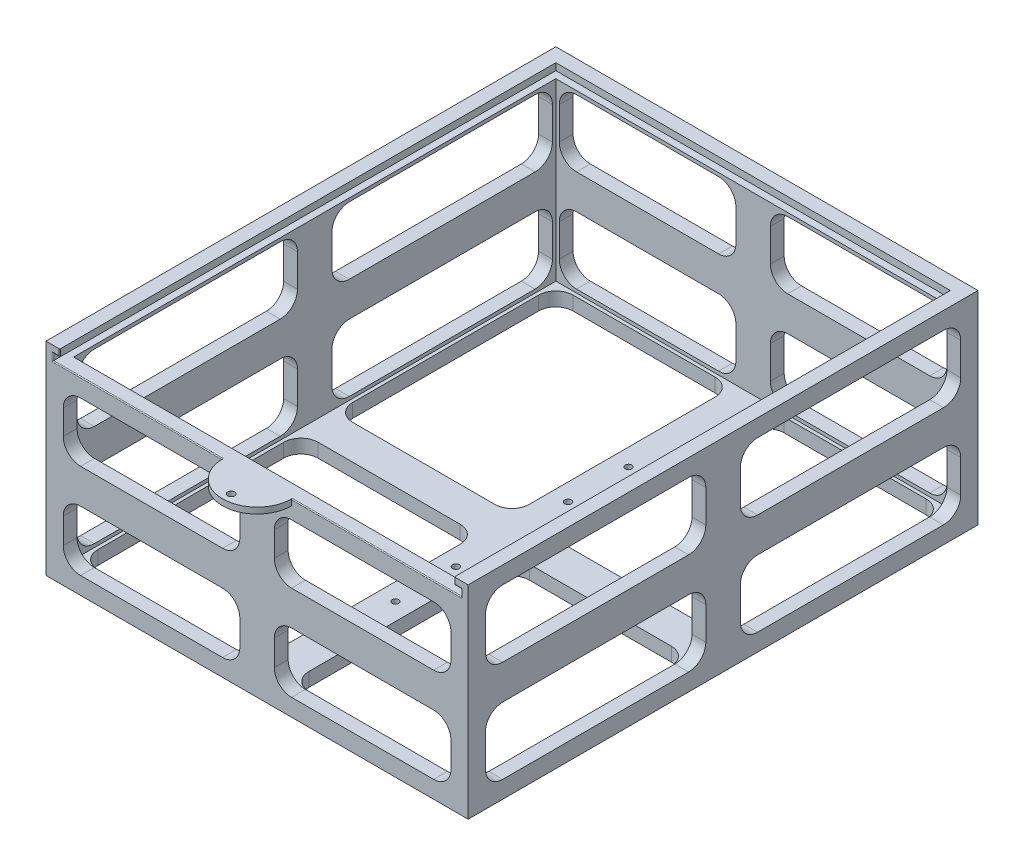
SolidWorks part; units mm, degrees
ref_plane "Front Plane" through (0, 0, 0) normal (0, 0, 1) x (1, 0, 0)
ref_plane "Top Plane" through (0, 0, 0) normal (0, 1, 0) x (1, 0, 0)
ref_plane "Right Plane" through (0, 0, 0) normal (1, 0, 0) x (0, 0, -1)
sketch "Sketch1" plane through (0, 0, 0) normal (0, 1, 0) x (1, 0, 0)
  line L1 (-122.3, -147.7) -> (122.3, -147.7)
  line L2 (-122.3, -147.7) -> (-122.3, 147.7)
  line L3 (-122.3, 147.7) -> (122.3, 147.7)
  line L4 (122.3, -147.7) -> (122.3, 147.7)
  line L5 (-122.3, -147.7) -> (122.3, 147.7) construction
  line L6 (-122.3, 147.7) -> (122.3, -147.7) construction
  point P0 (0, 0)
  dimension "D1" = 244.6
  dimension "D2" = 295.4
extrude "Boss-Extrude1" add sketch "Sketch1" along normal blind 117.6
shell "Shell1" thickness 8
sketch "Sketch5" plane through (122.3, 0, 0) normal (1, 0, 0) x (0, 0, -1)
  line L0 (-147.7, 117.6) -> (147.7, 0) construction
  line L1 (147.7, 117.6) -> (-147.7, 0) construction
  line L2 (-147.7, 117.6) -> (147.7, 117.6) construction
  line L3 (-137.7, 10) -> (137.7, 10)
  line L4 (-137.7, 10) -> (-137.7, 107.6)
  line L5 (-137.7, 107.6) -> (137.7, 107.6)
  line L6 (137.7, 10) -> (137.7, 107.6)
  line L7 (-137.7, 10) -> (137.7, 107.6) construction
  line L8 (-137.7, 107.6) -> (137.7, 10) construction
  line L9 (147.7, 117.6) -> (147.7, 0) construction
  point P8 (0, 58.8)
  dimension "D1" = 10
  dimension "D2" = 10
sketch "Sketch6" plane through (0, 0, 147.7) normal (0, 0, 1) x (1, 0, 0)
  line L0 (-122.3, 0) -> (122.3, 0) construction
  line L1 (-122.3, 117.6) -> (-122.3, 0) construction
  line L2 (-122.3, 117.6) -> (122.3, 117.6) construction
  line L3 (-112.3, 10) -> (112.3, 10)
  line L4 (-112.3, 10) -> (-112.3, 107.6)
  line L5 (-112.3, 107.6) -> (112.3, 107.6)
  line L6 (112.3, 10) -> (112.3, 107.6)
  line L7 (-112.3, 10) -> (112.3, 107.6) construction
  line L8 (-112.3, 107.6) -> (112.3, 10) construction
  line L9 (122.3, 10) -> (122.3, 107.6) construction
  point P8 (0, 58.8)
  dimension "D1" = 10
  dimension "D2" = 10
  dimension "D3" = 10
  dimension "D4" = 10
sketch "Sketch8" plane through (0, 0, 147.7) normal (0, 0, 1) x (1, 0, 0)
  line L0 (122.3, 117.6) -> (122.3, 0) construction
  line L1 (-114.3, 109.6) -> (114.3, 109.6)
  line L2 (-114.3, 109.6) -> (-114.3, 117.6)
  line L3 (-114.3, 117.6) -> (114.3, 117.6)
  line L4 (114.3, 109.6) -> (114.3, 117.6)
  line L5 (-122.3, 117.6) -> (-122.3, 0) construction
  line L6 (-122.3, 117.6) -> (122.3, 117.6) construction
  dimension "D1" = 8
  dimension "D2" = 8
  dimension "D3" = 0
  dimension "D4" = 8
extrude "Cut-Extrude1" cut sketch "Sketch8" against normal blind 8
sketch "Sketch9" plane through (0, 0, 147.7) normal (0, 0, 1) x (1, 0, 0)
  line L0 (122.3, 117.6) -> (122.3, 0) construction
  line L1 (-118.3, 109.6) -> (118.3, 109.6)
  line L2 (-118.3, 109.6) -> (-118.3, 113.6)
  line L3 (-118.3, 113.6) -> (118.3, 113.6)
  line L4 (118.3, 109.6) -> (118.3, 113.6)
  line L6 (-122.3, 117.6) -> (-122.3, 0) construction
  line L7 (-122.3, 117.6) -> (-114.3, 117.6) construction
  dimension "D1" = 4
  dimension "D2" = 4
  dimension "D3" = 8
  dimension "D4" = 4
extrude "Cut-Extrude2" cut sketch "Sketch9" against normal blind 291.4
sketch "Sketch10" plane through (0, 109.6, 0) normal (0, 1, 0) x (1, 0, 0)
  line L0 (-114.3, -147.7) -> (114.3, -147.7) construction
  line L1 (-20, -147.7) -> (20, -147.7)
  line L2 (-122.3, 147.7) -> (-122.3, -147.7) construction
  line L3 (122.3, -147.7) -> (122.3, 147.7) construction
  arc A0 (-20, -147.7) -> (20, -147.7) centre (0, -147.7) ccw
  dimension "D1" = 20
  dimension "D2" = 122.3
  dimension "D3" = 122.3
extrude "Boss-Extrude2" add sketch "Sketch10" against normal blind 3.5
sketch "Sketch12" plane through (0, 109.6, 0) normal (0, 1, 0) x (1, 0, 0)
  circle A0 centre (0, -162.7) radius 2
  arc A1 (-20, -147.7) -> (20, -147.7) centre (0, -147.7) ccw construction
  dimension "D2" = 4
  dimension "D1" = 15
extrude "Cut-Extrude3" cut sketch "Sketch12" against normal blind 3.5
fillet "Fillet1" radius 0.5 8 edges at (-114.3, 115.6, 147.7) (114.3, 115.6, 147.7) (116.3, 113.6, 147.7) (118.3, 111.6, 147.7) (69.15, 109.6, 147.7) (-69.15, 109.6, 147.7) (-116.3, 113.6, 147.7) (-118.3, 111.6, 147.7)
sketch "Sketch13" plane through (0, 0, 0) normal (0, -1, 0) x (1, 0, 0)
  line L0 (0, 0) -> (0, -147.7) construction
  line L1 (-122.3, 147.7) -> (122.3, -147.7) construction
  line L2 (-122.3, -147.7) -> (122.3, -147.7) construction
  line L3 (0, 0) -> (0, 147.7) construction
  line L4 (-122.3, 147.7) -> (122.3, 147.7) construction
  line L6 (-7.25, -72.5) -> (7.25, -72.5)
  line L7 (-7.25, -72.5) -> (-7.25, -27.5)
  line L8 (-7.25, -27.5) -> (7.25, -27.5)
  line L9 (7.25, -72.5) -> (7.25, -27.5)
  line L10 (-7.25, -72.5) -> (7.25, -27.5) construction
  line L11 (-7.25, -27.5) -> (7.25, -72.5) construction
  line L12 (-7.25, 27.5) -> (7.25, 27.5)
  line L13 (-7.25, 27.5) -> (-7.25, 72.5)
  line L14 (-7.25, 72.5) -> (7.25, 72.5)
  line L15 (7.25, 27.5) -> (7.25, 72.5)
  line L16 (-7.25, 27.5) -> (7.25, 72.5) construction
  line L17 (-7.25, 72.5) -> (7.25, 27.5) construction
  point P6 (0, -50)
  point P14 (0, 50)
  dimension "D1" = 50
  dimension "D2" = 147.7
  dimension "D3" = 50
  dimension "D4" = 14.5
  dimension "D5" = 14.5
  dimension "D6" = 45
  dimension "D7" = 45
extrude "Boss-Extrude3" add sketch "Sketch13" against normal blind 8
sketch "Sketch14" plane through (0, 0, 0) normal (0, -1, 0) x (1, 0, 0)
  line L4 (20, 147.7) -> (-20, 147.7) construction
  line L5 (122.3, -147.7) -> (-122.3, -147.7) construction
  circle A0 centre (0, 67.5) radius 1.95
  circle A1 centre (0, 32.5) radius 1.95
  circle A2 centre (0, -32.5) radius 1.95
  circle A3 centre (0, -67.5) radius 1.95
  dimension "D1" = 3.9
  dimension "D2" = 3.9
  dimension "D3" = 3.9
  dimension "D4" = 3.9
  dimension "D9" = 80.2
  dimension "D10" = 35
  dimension "D11" = 65
  dimension "D12" = 35
  dimension "D13" = 80.2
extrude "Cut-Extrude4" cut sketch "Sketch14" against normal blind 8
sketch "Sketch16" plane through (-122.3, 0, 0) normal (-1, 0, 0) x (0, 0, 1)
  line L0 (0, 117.6) -> (0, 0) construction
  line L1 (-127.7, 107.6) -> (-20, 107.6)
  line L2 (-137.7, 97.6) -> (-137.7, 78.8)
  line L3 (-127.7, 68.8) -> (-20, 68.8)
  line L4 (-10, 97.6) -> (-10, 78.8)
  line L5 (-127.7, 48.8) -> (-20, 48.8)
  line L6 (-137.7, 38.8) -> (-137.7, 20)
  line L7 (-127.7, 10) -> (-20, 10)
  line L8 (-10, 38.8) -> (-10, 20)
  line L9 (20, 107.6) -> (127.7, 107.6)
  line L10 (10, 97.6) -> (10, 78.8)
  line L11 (20, 68.8) -> (127.7, 68.8)
  line L12 (137.7, 97.6) -> (137.7, 78.8)
  line L13 (20, 48.8) -> (127.7, 48.8)
  line L14 (10, 38.8) -> (10, 20)
  line L15 (20, 10) -> (127.7, 10)
  line L16 (137.7, 38.8) -> (137.7, 20)
  line L17 (-147.7, 117.6) -> (147.7, 117.6) construction
  line L18 (-147.7, 0) -> (147.7, 0) construction
  line L19 (-147.7, 58.8) -> (147.7, 58.8) construction
  line L20 (-147.7, 117.6) -> (-147.7, 0) construction
  line L21 (147.7, 117.6) -> (147.7, 0) construction
  arc A0 (10, 78.8) -> (20, 68.8) centre (20, 78.8) ccw
  arc A1 (20, 107.6) -> (10, 97.6) centre (20, 97.6) ccw
  arc A2 (127.7, 107.6) -> (137.7, 97.6) centre (127.7, 97.6) cw
  arc A3 (127.7, 68.8) -> (137.7, 78.8) centre (127.7, 78.8) ccw
  arc A4 (127.7, 10) -> (137.7, 20) centre (127.7, 20) ccw
  arc A5 (127.7, 48.8) -> (137.7, 38.8) centre (127.7, 38.8) cw
  arc A6 (20, 48.8) -> (10, 38.8) centre (20, 38.8) ccw
  arc A7 (10, 20) -> (20, 10) centre (20, 20) ccw
  arc A8 (-20, 10) -> (-10, 20) centre (-20, 20) ccw
  arc A9 (-137.7, 20) -> (-127.7, 10) centre (-127.7, 20) ccw
  arc A10 (-127.7, 48.8) -> (-137.7, 38.8) centre (-127.7, 38.8) ccw
  arc A11 (-20, 48.8) -> (-10, 38.8) centre (-20, 38.8) cw
  arc A12 (-20, 68.8) -> (-10, 78.8) centre (-20, 78.8) ccw
  arc A13 (-137.7, 78.8) -> (-127.7, 68.8) centre (-127.7, 78.8) ccw
  arc A14 (-20, 107.6) -> (-10, 97.6) centre (-20, 97.6) cw
  arc A15 (-127.7, 107.6) -> (-137.7, 97.6) centre (-127.7, 97.6) ccw
  dimension "D17" = 10
  dimension "D1" = 20
  dimension "D2" = 10
  dimension "D3" = 10
  dimension "D4" = 10
  dimension "D5" = 10
  dimension "D6" = 20
  dimension "D7" = 10
  dimension "D8" = 20
  dimension "D9" = 10
  dimension "D10" = 20
  dimension "D11" = 10
  dimension "D12" = 10
  dimension "D13" = 10
  dimension "D14" = 10
  dimension "D15" = 10
  dimension "D16" = 10
extrude "Cut-Extrude5" cut sketch "Sketch16" against normal blind 300
sketch "Sketch17" plane through (0, 0, -147.7) normal (0, 0, -1) x (-1, 0, 0)
  line L0 (0, 117.6) -> (0, 0) construction
  line L1 (-122.3, 117.6) -> (122.3, 117.6) construction
  line L2 (-122.3, 58.8) -> (122.3, 58.8) construction
  line L3 (-122.3, 117.6) -> (-122.3, 0) construction
  line L4 (122.3, 117.6) -> (122.3, 0) construction
  line L5 (-122.3, 0) -> (122.3, 0) construction
  line L6 (-102.3, 107.6) -> (-20, 107.6)
  line L7 (-112.3, 97.6) -> (-112.3, 78.8)
  line L8 (-102.3, 68.8) -> (-20, 68.8)
  line L9 (-10, 97.6) -> (-10, 78.8)
  line L10 (-102.3, 48.8) -> (-20, 48.8)
  line L11 (-112.3, 38.8) -> (-112.3, 20)
  line L12 (-102.3, 10) -> (-20, 10)
  line L13 (-10, 38.8) -> (-10, 20)
  line L14 (20, 107.6) -> (102.3, 107.6)
  line L15 (10, 97.6) -> (10, 78.8)
  line L16 (20, 68.8) -> (102.3, 68.8)
  line L17 (112.3, 97.6) -> (112.3, 78.8)
  line L18 (20, 48.8) -> (102.3, 48.8)
  line L19 (10, 38.8) -> (10, 20)
  line L20 (20, 10) -> (102.3, 10)
  line L21 (112.3, 38.8) -> (112.3, 20)
  arc A0 (102.3, 68.8) -> (112.3, 78.8) centre (102.3, 78.8) ccw
  arc A1 (102.3, 107.6) -> (112.3, 97.6) centre (102.3, 97.6) cw
  arc A2 (20, 107.6) -> (10, 97.6) centre (20, 97.6) ccw
  arc A3 (10, 78.8) -> (20, 68.8) centre (20, 78.8) ccw
  arc A4 (102.3, 10) -> (112.3, 20) centre (102.3, 20) ccw
  arc A5 (102.3, 48.8) -> (112.3, 38.8) centre (102.3, 38.8) cw
  arc A6 (20, 48.8) -> (10, 38.8) centre (20, 38.8) ccw
  arc A7 (10, 20) -> (20, 10) centre (20, 20) ccw
  arc A8 (-20, 10) -> (-10, 20) centre (-20, 20) ccw
  arc A9 (-20, 48.8) -> (-10, 38.8) centre (-20, 38.8) cw
  arc A10 (-112.3, 20) -> (-102.3, 10) centre (-102.3, 20) ccw
  arc A11 (-102.3, 48.8) -> (-112.3, 38.8) centre (-102.3, 38.8) ccw
  arc A12 (-20, 68.8) -> (-10, 78.8) centre (-20, 78.8) ccw
  arc A13 (-20, 107.6) -> (-10, 97.6) centre (-20, 97.6) cw
  arc A14 (-112.3, 78.8) -> (-102.3, 68.8) centre (-102.3, 78.8) ccw
  arc A15 (-102.3, 107.6) -> (-112.3, 97.6) centre (-102.3, 97.6) ccw
  dimension "D17" = 10
  dimension "D1" = 10
  dimension "D2" = 10
  dimension "D3" = 10
  dimension "D4" = 10
  dimension "D5" = 10
  dimension "D6" = 10
  dimension "D7" = 10
  dimension "D8" = 10
  dimension "D9" = 10
  dimension "D10" = 10
  dimension "D11" = 10
  dimension "D12" = 10
  dimension "D13" = 10
  dimension "D14" = 10
  dimension "D15" = 10
  dimension "D16" = 10
extrude "Cut-Extrude6" cut sketch "Sketch17" against normal blind 8
sketch "Sketch18" plane through (0, 0, 0) normal (0, -1, 0) x (1, 0, 0)
  line L0 (0, 147.7) -> (0, -147.7) construction
  line L1 (20, 147.7) -> (-20, 147.7) construction
  line L2 (122.3, -147.7) -> (-122.3, -147.7) construction
  line L3 (-122.3, 0) -> (122.3, 0) construction
  line L4 (-122.3, -147.7) -> (-122.3, 147.7) construction
  line L5 (122.3, 147.7) -> (122.3, -147.7) construction
  line L6 (-122.3, 147.7) -> (122.3, 147.7) construction
  line L7 (-102.3, 137.7) -> (-20, 137.7)
  line L8 (-112.3, 127.7) -> (-112.3, 20)
  line L9 (-102.3, 10) -> (-20, 10)
  line L10 (-10, 127.7) -> (-10, 20)
  line L11 (-102.3, -10) -> (-20, -10)
  line L12 (-112.3, -20) -> (-112.3, -127.7)
  line L13 (-102.3, -137.7) -> (-20, -137.7)
  line L14 (-10, -20) -> (-10, -127.7)
  line L15 (20, 137.7) -> (102.3, 137.7)
  line L16 (10, 127.7) -> (10, 20)
  line L17 (20, 10) -> (102.3, 10)
  line L18 (112.3, 127.7) -> (112.3, 20)
  line L19 (20, -10) -> (102.3, -10)
  line L20 (10, -20) -> (10, -127.7)
  line L21 (20, -137.7) -> (102.3, -137.7)
  line L22 (112.3, -20) -> (112.3, -127.7)
  arc A0 (10, -127.7) -> (20, -137.7) centre (20, -127.7) ccw
  arc A1 (102.3, -137.7) -> (112.3, -127.7) centre (102.3, -127.7) ccw
  arc A2 (102.3, -10) -> (112.3, -20) centre (102.3, -20) cw
  arc A3 (20, -10) -> (10, -20) centre (20, -20) ccw
  arc A4 (-20, -137.7) -> (-10, -127.7) centre (-20, -127.7) ccw
  arc A5 (-112.3, -127.7) -> (-102.3, -137.7) centre (-102.3, -127.7) ccw
  arc A6 (-20, -10) -> (-10, -20) centre (-20, -20) cw
  arc A7 (-102.3, -10) -> (-112.3, -20) centre (-102.3, -20) ccw
  arc A8 (102.3, 137.7) -> (112.3, 127.7) centre (102.3, 127.7) cw
  arc A9 (102.3, 10) -> (112.3, 20) centre (102.3, 20) ccw
  arc A10 (10, 20) -> (20, 10) centre (20, 20) ccw
  arc A11 (20, 137.7) -> (10, 127.7) centre (20, 127.7) ccw
  arc A12 (-20, 137.7) -> (-10, 127.7) centre (-20, 127.7) cw
  arc A13 (-20, 10) -> (-10, 20) centre (-20, 20) ccw
  arc A14 (-112.3, 20) -> (-102.3, 10) centre (-102.3, 20) ccw
  arc A15 (-102.3, 137.7) -> (-112.3, 127.7) centre (-102.3, 127.7) ccw
  dimension "D17" = 10
  dimension "D1" = 10
  dimension "D2" = 10
  dimension "D3" = 10
  dimension "D4" = 10
  dimension "D5" = 10
  dimension "D6" = 10
  dimension "D7" = 10
  dimension "D8" = 10
  dimension "D9" = 10
  dimension "D10" = 10
  dimension "D11" = 10
  dimension "D12" = 10
  dimension "D13" = 10
  dimension "D14" = 10
  dimension "D15" = 10
  dimension "D16" = 10
extrude "Cut-Extrude7" cut sketch "Sketch18" against normal blind 8
sketch "Sketch19" plane through (0, 0, 147.7) normal (0, 0, 1) x (1, 0, 0)
  line L0 (0, 109.6) -> (0, 0) construction
  line L1 (-118.3, 109.6) -> (118.3, 109.6) construction
  line L2 (0, 54.8) -> (-122.3, 54.8) construction
  line L3 (-122.3, 117.6) -> (-122.3, 0) construction
  line L4 (0, 54.8) -> (122.3, 54.8) construction
  line L5 (122.3, 117.6) -> (122.3, 0) construction
  line L6 (-20, 109.1) -> (-118.8, 109.1) construction
  line L7 (-102.3, 99.1) -> (-20, 99.1)
  line L8 (-112.3, 89.1) -> (-112.3, 74.8)
  line L9 (-102.3, 64.8) -> (-20, 64.8)
  line L10 (-10, 89.1) -> (-10, 74.8)
  line L11 (20, 99.1) -> (102.3, 99.1)
  line L12 (10, 89.1) -> (10, 74.8)
  line L13 (20, 64.8) -> (102.3, 64.8)
  line L14 (112.3, 89.1) -> (112.3, 74.8)
  line L15 (-102.3, 44.8) -> (-20, 44.8)
  line L16 (-112.3, 34.8) -> (-112.3, 20)
  line L17 (-102.3, 10) -> (-20, 10)
  line L18 (-10, 34.8) -> (-10, 20)
  line L19 (20, 44.8) -> (102.3, 44.8)
  line L20 (10, 34.8) -> (10, 20)
  line L21 (20, 10) -> (102.3, 10)
  line L22 (112.3, 34.8) -> (112.3, 20)
  line L23 (118.8, 109.1) -> (20, 109.1) construction
  line L24 (-122.3, 0) -> (122.3, 0) construction
  arc A0 (102.3, 99.1) -> (112.3, 89.1) centre (102.3, 89.1) cw
  arc A1 (102.3, 64.8) -> (112.3, 74.8) centre (102.3, 74.8) ccw
  arc A2 (102.3, 10) -> (112.3, 20) centre (102.3, 20) ccw
  arc A3 (102.3, 44.8) -> (112.3, 34.8) centre (102.3, 34.8) cw
  arc A4 (10, 20) -> (20, 10) centre (20, 20) ccw
  arc A5 (20, 44.8) -> (10, 34.8) centre (20, 34.8) ccw
  arc A6 (-20, 44.8) -> (-10, 34.8) centre (-20, 34.8) cw
  arc A7 (-20, 10) -> (-10, 20) centre (-20, 20) ccw
  arc A8 (-112.3, 20) -> (-102.3, 10) centre (-102.3, 20) ccw
  arc A9 (-102.3, 44.8) -> (-112.3, 34.8) centre (-102.3, 34.8) ccw
  arc A10 (10, 74.8) -> (20, 64.8) centre (20, 74.8) ccw
  arc A11 (20, 99.1) -> (10, 89.1) centre (20, 89.1) ccw
  arc A12 (-20, 99.1) -> (-10, 89.1) centre (-20, 89.1) cw
  arc A13 (-20, 64.8) -> (-10, 74.8) centre (-20, 74.8) ccw
  arc A14 (-112.3, 74.8) -> (-102.3, 64.8) centre (-102.3, 74.8) ccw
  arc A15 (-102.3, 99.1) -> (-112.3, 89.1) centre (-102.3, 89.1) ccw
  dimension "D17" = 10
  dimension "D1" = 10
  dimension "D2" = 10
  dimension "D3" = 10
  dimension "D4" = 10
  dimension "D5" = 10
  dimension "D6" = 10
  dimension "D7" = 10
  dimension "D8" = 10
  dimension "D9" = 10
  dimension "D10" = 10
  dimension "D11" = 10
  dimension "D12" = 10
  dimension "D13" = 10
  dimension "D14" = 10
  dimension "D15" = 10
  dimension "D16" = 10
extrude "Cut-Extrude8" cut sketch "Sketch19" against normal blind 8
